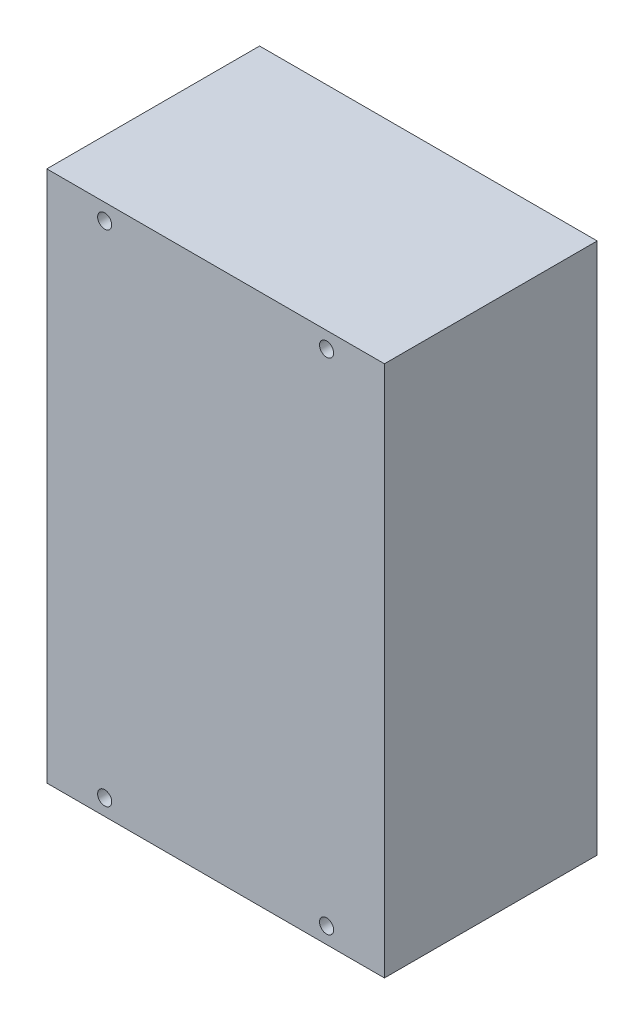
SolidWorks part; units mm, degrees
ref_plane "Front Plane" through (0, 0, 0) normal (0, 0, 1) x (1, 0, 0)
ref_plane "Top Plane" through (0, 0, 0) normal (0, 1, 0) x (1, 0, 0)
ref_plane "Right Plane" through (0, 0, 0) normal (1, 0, 0) x (0, 0, -1)
sketch "Sketch1" plane through (0, 0, 0) normal (0, 0, 1) x (1, 0, 0)
  line L0 (0, 62.23) -> (0, 0) construction
  line L1 (-39.497, 62.23) -> (39.497, 62.23)
  line L2 (-39.497, 62.23) -> (-39.497, -62.23)
  line L3 (-39.497, -62.23) -> (39.497, -62.23)
  line L4 (39.497, 62.23) -> (39.497, -62.23)
  line L5 (-39.497, 62.23) -> (39.497, -62.23) construction
  line L6 (-39.497, -62.23) -> (39.497, 62.23) construction
  line L7 (-19.05, 54.6608) -> (19.05, 54.6608) construction
  line L8 (-19.05, 54.6608) -> (-19.05, 62.23) construction
  line L9 (-19.05, 62.23) -> (19.05, 62.23) construction
  line L10 (19.05, 54.6608) -> (19.05, 62.23) construction
  line L11 (-19.05, 54.6608) -> (19.05, 62.23) construction
  line L12 (-19.05, 62.23) -> (19.05, 54.6608) construction
  line L13 (-39.497, 0) -> (39.497, 0) construction
  line L14 (-32.8676, 62.23) -> (-19.05, 62.23) construction
  line L15 (-32.8676, 62.23) -> (-32.8676, 54.6608) construction
  line L16 (-32.8676, 54.6608) -> (-19.05, 54.6608) construction
  line L17 (-19.05, 62.23) -> (-19.05, 54.6608) construction
  line L18 (-32.8676, 62.23) -> (-19.05, 54.6608) construction
  line L19 (-32.8676, 54.6608) -> (-19.05, 62.23) construction
  circle A0 centre (-25.9588, 58.4454) radius 1.651
  circle A1 centre (25.9588, 58.4454) radius 1.651
  circle A2 centre (25.9588, -58.4454) radius 1.651
  circle A3 centre (-25.9588, -58.4454) radius 1.651
  point P0 (0, 0)
  point P8 (0, 58.4454)
  point P15 (-25.9588, 58.4454)
  dimension "D3" = 3.302
  dimension "D1" = 78.994
  dimension "D2" = 124.46
  dimension "D4" = 38.1
  dimension "D5" = 13.8176
  dimension "D6" = 3.7846
extrude "Boss-Extrude1" add sketch "Sketch1" along normal blind 49.784
equation "\"D6@Sketch1\"=0.084+0.5*0.13"
